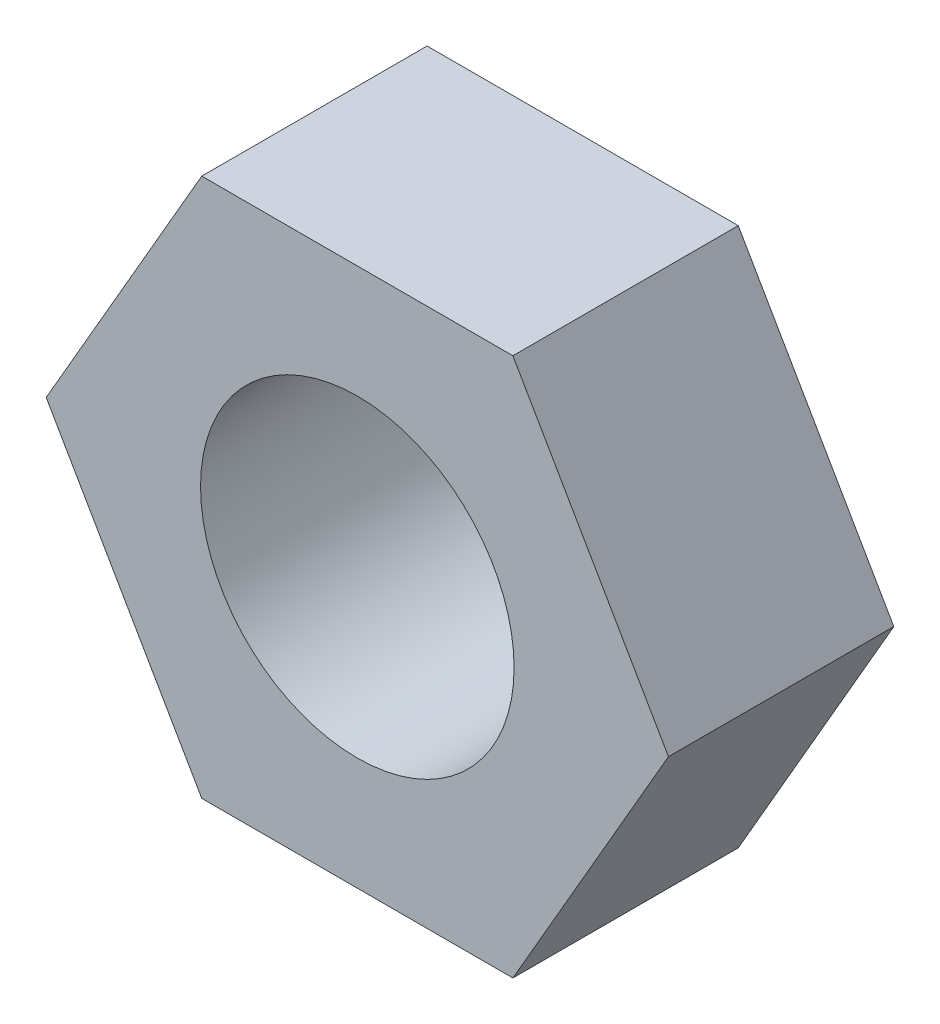
SolidWorks part; units mm, degrees
ref_plane "Plano frontal" through (0, 0, 0) normal (0, 0, 1) x (1, 0, 0)
ref_plane "Plano superior" through (0, 0, 0) normal (0, 1, 0) x (1, 0, 0)
ref_plane "Plano direito" through (0, 0, 0) normal (1, 0, 0) x (0, 0, -1)
sketch "Esboço1" plane through (0, 0, 0) normal (0, 0, 1) x (1, 0, 0)
  line L1 (1.5877, 2.75) -> (-1.5877, 2.75)
  line L2 (-1.5877, 2.75) -> (-3.1754, 0)
  line L3 (-3.1754, 0) -> (-1.5877, -2.75)
  line L4 (-1.5877, -2.75) -> (1.5877, -2.75)
  line L5 (1.5877, -2.75) -> (3.1754, 0)
  line L6 (3.1754, 0) -> (1.5877, 2.75)
  circle A0 centre (0, 0) radius 2.75 construction
  circle A1 centre (0, 0) radius 1.6
  dimension "D2" = 3.2
  dimension "D1" = 5.5
extrude "Ressalto-extrusão1" add sketch "Esboço1" along normal blind 2.3
